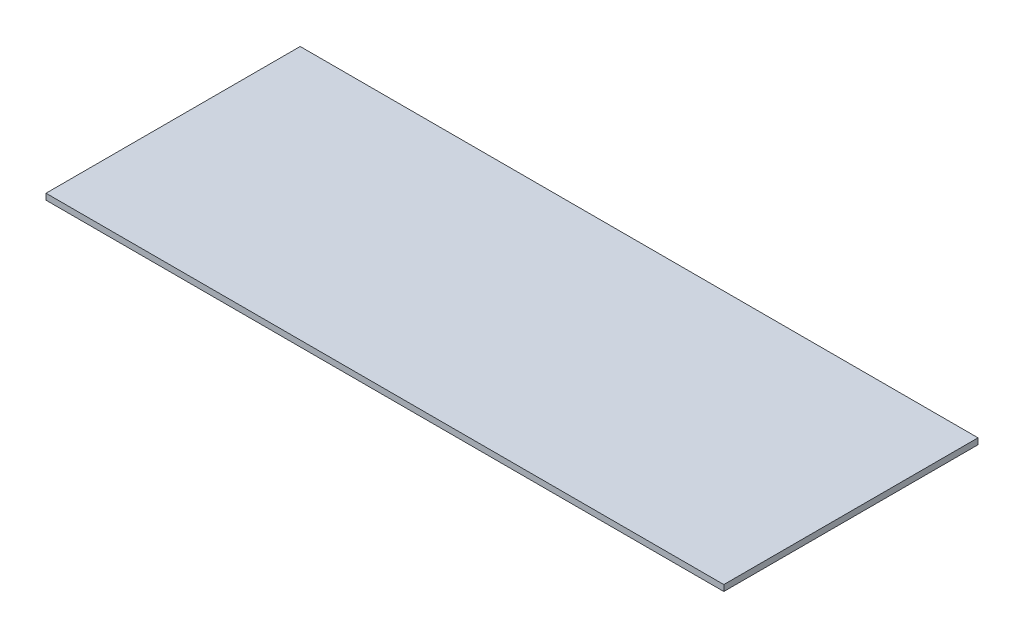
SolidWorks part; units mm, degrees
material "Acrylic (Medium-high impact)"
ref_plane "Front Plane" through (0, 0, 0) normal (0, 0, 1) x (1, 0, 0)
ref_plane "Top Plane" through (0, 0, 0) normal (0, 1, 0) x (1, 0, 0)
ref_plane "Right Plane" through (0, 0, 0) normal (1, 0, 0) x (0, 0, -1)
sketch "Sketch1" plane through (0, 0, 0) normal (0, 1, 0) x (1, 0, 0)
  line L1 (-177.8, -66.675) -> (177.8, -66.675)
  line L2 (-177.8, -66.675) -> (-177.8, 66.675)
  line L3 (-177.8, 66.675) -> (177.8, 66.675)
  line L4 (177.8, -66.675) -> (177.8, 66.675)
  line L5 (-177.8, -66.675) -> (177.8, 66.675) construction
  line L6 (-177.8, 66.675) -> (177.8, -66.675) construction
  point P0 (0, 0)
  dimension "D1" = 355.6
  dimension "D2" = 133.35
extrude "Boss-Extrude1" add sketch "Sketch1" along normal mid plane 3.175
